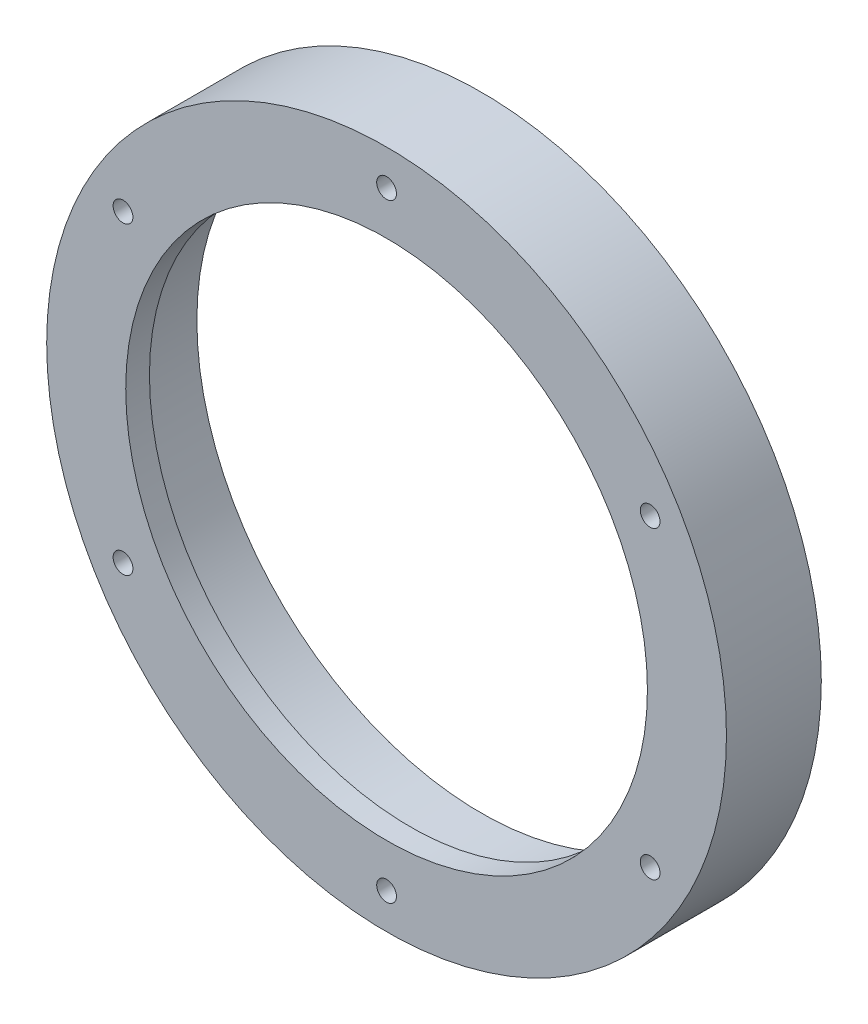
SolidWorks part; units mm, degrees
material "6061-T6 (SS)"
ref_plane "前视基准面" through (0, 0, 0) normal (0, 0, 1) x (1, 0, 0)
ref_plane "上视基准面" through (0, 0, 0) normal (0, 1, 0) x (1, 0, 0)
ref_plane "右视基准面" through (0, 0, 0) normal (1, 0, 0) x (0, 0, -1)
sketch "草图1" plane through (0, 0, 0) normal (0, 0, 1) x (1, 0, 0)
  circle A0 centre (0, 0) radius 43
  circle A1 centre (0, 0) radius 36
  dimension "D1" = 86
  dimension "D2" = 72
extrude "凸台-拉伸1" add sketch "草图1" along normal blind 9
sketch "草图2" plane through (0, 0, 9) normal (0, 0, 1) x (1, 0, 0)
  circle A2 centre (0, 0) radius 33
  circle A3 centre (0, 0) radius 43
  dimension "D1" = 66
  dimension "D2" = 86
extrude "凸台-拉伸2" add sketch "草图2" along normal blind 3
sketch "草图3" plane through (0, 0, 0) normal (0, 0, -1) x (-1, 0, 0)
  circle A0 centre (0, 0) radius 38.5 construction
  circle A1 centre (0, 0) radius 43 construction
  point P4 (0, 38.5)
  point P7 (33.342, 19.25)
  point P10 (33.342, -19.25)
  point P11 (0, -38.5)
  point P12 (-33.342, -19.25)
  point P13 (-33.342, 19.25)
  dimension "D1" = 77
  dimension "D2" = 6
hole_wizard "M3 螺纹孔1" positions "3D草图1" profile "草图4" tap size "M3" standard "GB" end condition through all
sketch3d "3D草图1"
  point P0 (-33.342, 19.25, 0)
  point P3 (0, 38.5, 0)
  point P6 (33.342, 19.25, 0)
  point P9 (33.342, -19.25, 0)
  point P12 (0, -38.5, 0)
  point P15 (-33.342, -19.25, 0)
sketch "草图4" plane through (-33.342, 19.25, 0) normal (1, 0, 0) x (0, 1, 0)
  line L0 (0, 0) -> (0, 12)
  line L1 (0, 12) -> (1.25, 12)
  line L2 (1.25, 12) -> (1.25, 0)
  line L5 (1.25, 0) -> (0, 0)
  line L11 (0, -6.35) -> (0, 107.95) construction
  dimension "通孔螺纹孔钻头直径" = 2.5
  dimension "通孔螺纹孔钻头深度" = 12
cosmetic thread "孔螺蚊线1"
cosmetic thread "孔螺蚊线2"
cosmetic thread "孔螺蚊线3"
cosmetic thread "孔螺蚊线4"
cosmetic thread "孔螺蚊线5"
cosmetic thread "孔螺蚊线6"
